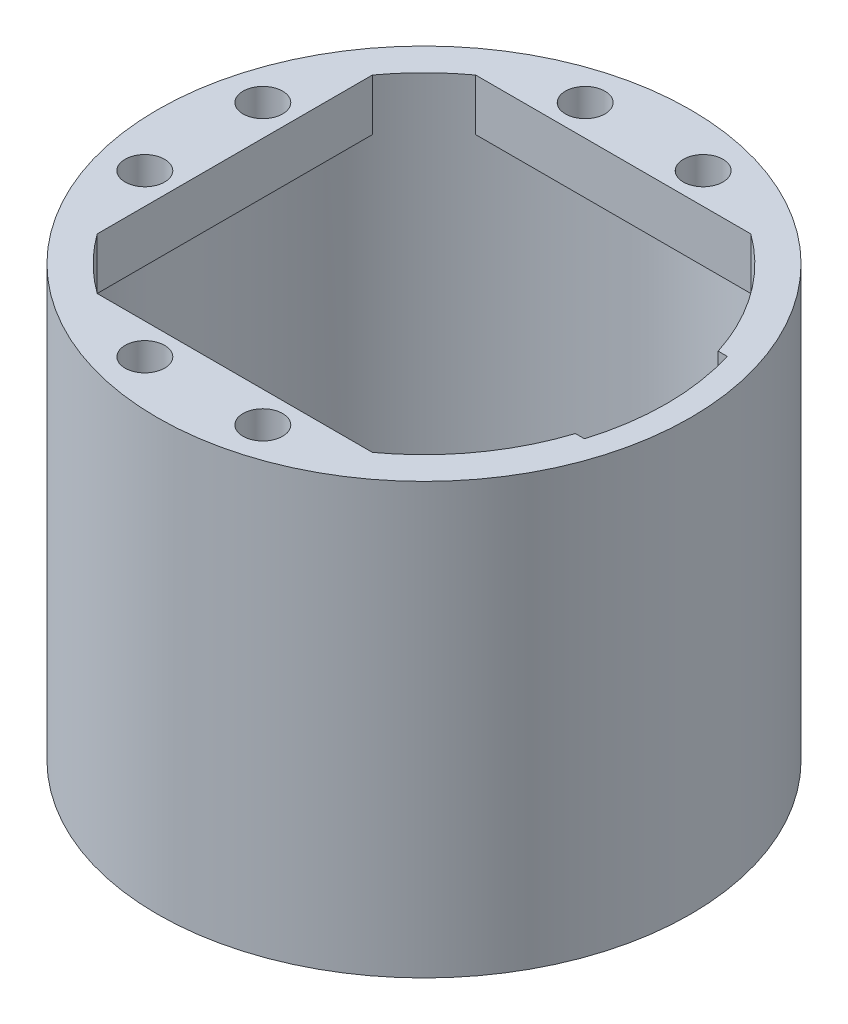
SolidWorks part; units mm, degrees
ref_plane "Front Plane" through (0, 0, 0) normal (0, 0, 1) x (1, 0, 0)
ref_plane "Top Plane" through (0, 0, 0) normal (0, 1, 0) x (1, 0, 0)
ref_plane "Right Plane" through (0, 0, 0) normal (1, 0, 0) x (0, 0, -1)
sketch "Sketch1" plane through (0, 0, 0) normal (0, 1, 0) x (1, 0, 0)
  line L0 (25.9027, -8.3) -> (26.9509, -8.3)
  line L1 (25.9027, 8.3) -> (26.9509, 8.3)
  circle A0 centre (0, 0) radius 31
  arc A1 (25.9027, 8.3) -> (25.9027, -8.3) centre (0, 0) ccw
  arc A2 (26.9509, -8.3) -> (26.9509, 8.3) centre (0, 0) ccw
extrude "Boss-Extrude1" add sketch "Sketch1" against normal blind 50
sketch "Sketch2" plane through (0, 0, 0) normal (0, 1, 0) x (1, 0, 0)
  line L1 (15.995, -22) -> (-15.995, -22)
  line L2 (-15.995, 22) -> (15.995, 22)
  line L3 (-22, -15.995) -> (-22, 15.995)
  line L4 (22, 15.995) -> (22, -15.995) [skipped]
  arc A0 (15.995, 22) -> (-15.995, 22) centre (0, 0) ccw
  arc A2 (-15.995, -22) -> (15.995, -22) centre (0, 0) ccw
  arc A3 (-22, 15.995) -> (-22, -15.995) centre (0, 0) ccw
  arc A4 (22, -15.995) -> (22, 15.995) centre (0, 0) ccw [skipped]
  point P13 (0, 0)
  dimension "D1" = 4
extrude "Boss-Extrude2" add sketch "Sketch2" against normal blind 6
sketch "Sketch3" plane through (0, 0, 0) normal (0, 1, 0) x (1, 0, 0)
  circle A0 centre (-25.597, 6.8587) radius 2.3
  circle A2 centre (-32.4557, 5.0209) radius 2.3 [skipped]
  circle A3 centre (-25.597, -6.8587) radius 2.3
  circle A4 centre (-6.8587, 25.597) radius 2.3
  circle A5 centre (6.8587, 25.597) radius 2.3
  circle A8 centre (6.8587, -25.597) radius 2.3
  circle A9 centre (-6.8587, -25.597) radius 2.3
  circle A10 centre (25.597, 6.8587) radius 2.3 [skipped]
  circle A11 centre (25.597, -6.8587) radius 2.3 [skipped]
  point P5 (-25.597, -6.8587)
  point P8 (-25.597, -6.8587)
  point P13 (0, 0)
  point P26 (0, 0)
  dimension "D1" = 2
  dimension "D2" = 2
  dimension "D3" = 4
extrude "Cut-Extrude1" cut sketch "Sketch3" against normal blind 4
